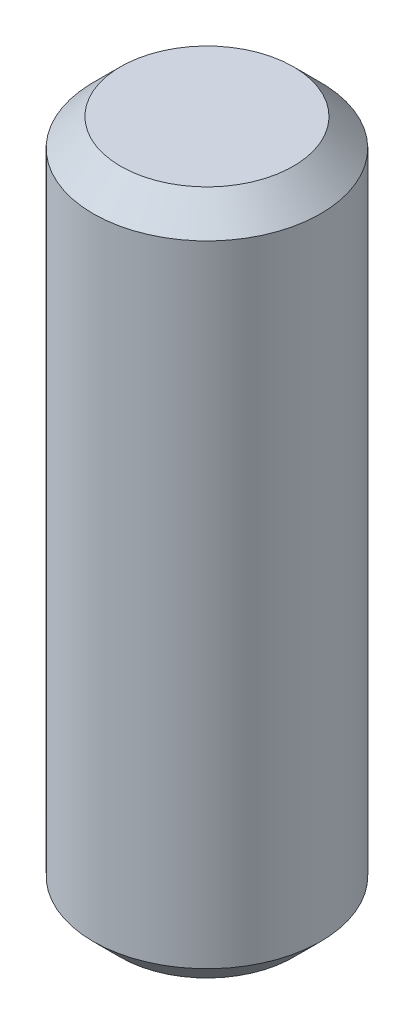
SolidWorks part; units mm, degrees
ref_plane "Front Plane" through (0, 0, 0) normal (0, 0, 1) x (1, 0, 0)
ref_plane "Top Plane" through (0, 0, 0) normal (0, 1, 0) x (1, 0, 0)
ref_plane "Right Plane" through (0, 0, 0) normal (1, 0, 0) x (0, 0, -1)
sketch "Sketch1" plane through (0, 0, 0) normal (0, 1, 0) x (1, 0, 0)
  circle A0 centre (0, 0) radius 4.15
  dimension "D1" = 8.3
extrude "Boss-Extrude1" add sketch "Sketch1" along normal blind 25
sketch "Sketch2" plane through (0, 25, 0) normal (0, 1, 0) x (1, 0, 0)
  line L0 (-4.15, 0) -> (0, 0) construction
  line L1 (-5, 5) -> (5, 5) construction
  line L2 (-5, -5) -> (5, -5) construction
  line L3 (0, 0) -> (4.15, 0) construction
  line L9 (-7.1342, -5) -> (7.1342, 5) construction
  line L10 (-7.1342, 5) -> (7.1342, -5) construction
  line L11 (-5, -5) -> (5, -5)
  line L12 (-5, -5) -> (-5, 5)
  line L13 (-5, 5) -> (5, 5)
  line L14 (5, -5) -> (5, 5)
  line L15 (-5, -5) -> (5, 5) construction
  line L16 (-5, 5) -> (5, -5) construction
  arc A0 (5, -5) -> (5, 5) centre (5, 0) ccw construction
  arc A1 (-5, 5) -> (-5, -5) centre (-5, 0) ccw construction
  circle A2 centre (0, 0) radius 4.15 construction
  arc A3 (0, 0) -> (-5, 5) centre (-5, 0) ccw construction
  arc A4 (-5, -5) -> (0, 0) centre (-5, 0) ccw construction
  arc A5 (5, 5) -> (0, 0) centre (5, 0) ccw construction
  arc A6 (0, 0) -> (5, -5) centre (5, 0) ccw construction
  dimension "D1" = 10
  dimension "D2" = 5
  dimension "D3" = 5
  dimension "D4" = 10
  dimension "D5" = 14.2684
  dimension "D6" = 10
  dimension "D7" = 10
chamfer "Chamfer2" distance 1 angle 45 2 edges at (0, 0, 4.15) (0, 25, 4.15)
